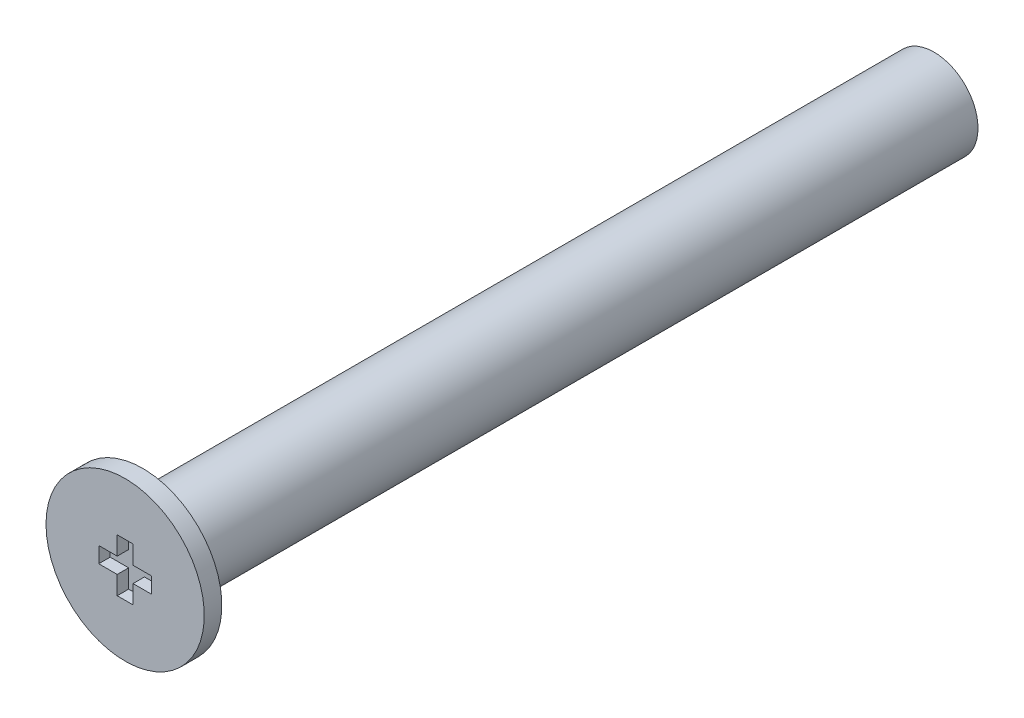
SolidWorks part; units mm, degrees
ref_plane "前视基准面" through (0, 0, 0) normal (0, 0, 1) x (1, 0, 0)
ref_plane "上视基准面" through (0, 0, 0) normal (0, 1, 0) x (1, 0, 0)
ref_plane "右视基准面" through (0, 0, 0) normal (1, 0, 0) x (0, 0, -1)
other "Configuration Table"
sketch "草图1" plane through (0, 0, 0) normal (0, 0, 1) x (1, 0, 0)
  circle A0 centre (0, 0) radius 2.5
extrude "标准杆径_头下长度" add sketch "草图1" against normal blind 45
sketch "草图2" plane through (0, 0, 0) normal (0, 0, 1) x (1, 0, 0)
  circle A0 centre (0, 0) radius 4.25
sketch "草图4" plane through (0, 0, 0) normal (0, 1, 0) x (1, 0, 0)
  line L0 (0, 0) -> (5.9, 0)
  line L1 (5.9, 0) -> (5.9, -0.3477)
  line L2 (0, -3.1) -> (0, 0)
  line L3 (0, 2) -> (0, -5.1) construction
  arc A0 (5.9, -0.3477) -> (0, -3.1) centre (0, 4.6) cw
sketch "草图5" plane through (0, 0, 0) normal (0, 0, 1) x (1, 0, 0)
  line L0 (-0.5, -2.5) -> (0.5, -2.5)
  line L1 (0.5, -2.5) -> (0.5, -0.5)
  line L2 (0.5, -0.5) -> (2.5, -0.5)
  line L3 (2.5, -0.5) -> (2.5, 0.5)
  line L4 (2.5, 0.5) -> (0.5, 0.5)
  line L5 (0.5, 0.5) -> (0.5, 2.5)
  line L6 (0.5, 2.5) -> (-0.5, 2.5)
  line L7 (-0.5, 2.5) -> (-0.5, 0.5)
  line L8 (-0.5, 0.5) -> (-2.5, 0.5)
  line L9 (-2.5, 0.5) -> (-2.5, -0.5)
  line L10 (-2.5, -0.5) -> (-0.5, -0.5)
  line L11 (-0.5, -0.5) -> (-0.5, -2.5)
sketch "草图6" plane through (0, 0, 0) normal (0, 1, 0) x (1, 0, 0)
  line L0 (0, 0) -> (4.5, 0)
  line L1 (4.5, 0) -> (4.5, -1)
  line L2 (4.5, -1) -> (0, -1)
  line L3 (0, -1) -> (0, 0)
  line L4 (0, 2) -> (0, -3) construction
revolve "已确认_十字槽超薄头" add sketch "草图6" angle 360 about L4
sketch "草图7" plane through (0, 0, 0) normal (0, 0, 1) x (1, 0, 0)
  line L0 (-0.45, -1.5) -> (0.45, -1.5)
  line L1 (0.45, -1.5) -> (0.45, -0.45)
  line L2 (0.45, -0.45) -> (1.5, -0.45)
  line L3 (1.5, -0.45) -> (1.5, 0.45)
  line L4 (1.5, 0.45) -> (0.45, 0.45)
  line L5 (0.45, 0.45) -> (0.45, 1.5)
  line L6 (0.45, 1.5) -> (-0.45, 1.5)
  line L7 (-0.45, 1.5) -> (-0.45, 0.45)
  line L8 (-0.45, 0.45) -> (-1.5, 0.45)
  line L9 (-1.5, 0.45) -> (-1.5, -0.45)
  line L10 (-1.5, -0.45) -> (-0.45, -0.45)
  line L11 (-0.45, -0.45) -> (-0.45, -1.5)
extrude "十字槽_PH2_简化" cut sketch "草图7" against normal blind 0.66 from offset 1.01
